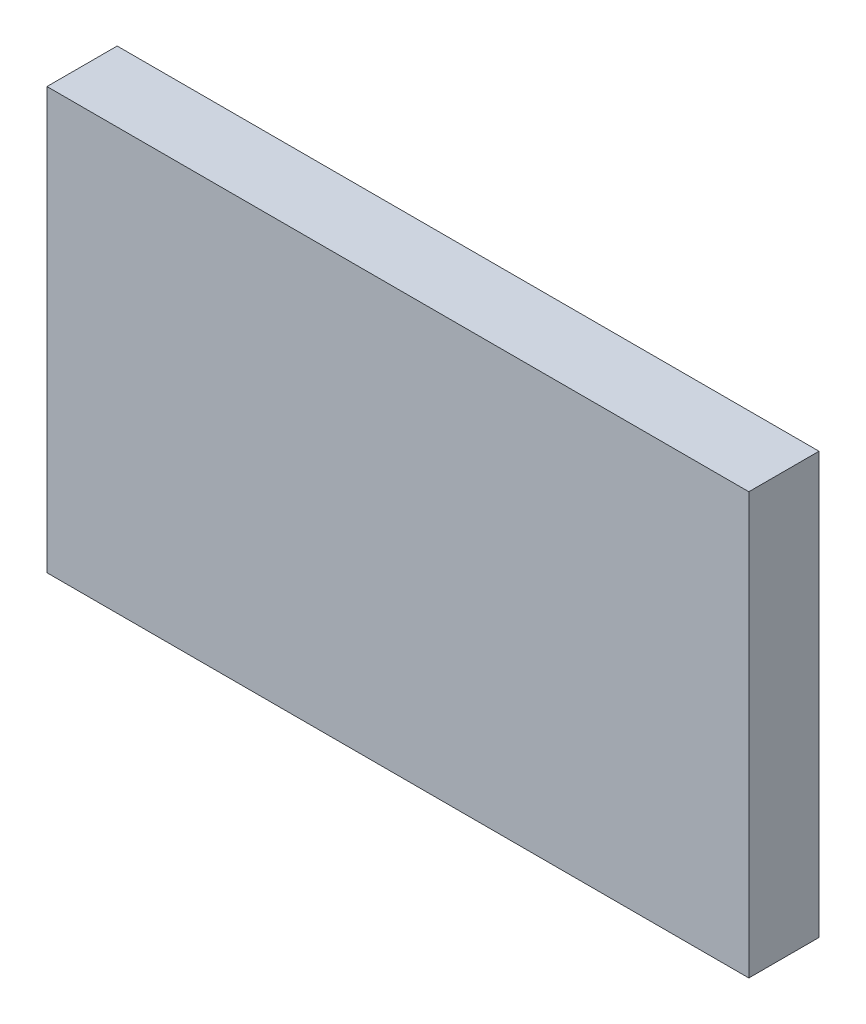
SolidWorks part; units mm, degrees
ref_plane "前视基准面" through (0, 0, 0) normal (0, 0, 1) x (1, 0, 0)
ref_plane "上视基准面" through (0, 0, 0) normal (0, 1, 0) x (1, 0, 0)
ref_plane "右视基准面" through (0, 0, 0) normal (1, 0, 0) x (0, 0, -1)
other "Configuration Table"
sketch "草图1" plane through (0, 0, 0) normal (0, 0, 1) x (1, 0, 0)
  line L1 (-250, -150) -> (250, -150)
  line L2 (-250, -150) -> (-250, 150)
  line L3 (-250, 150) -> (250, 150)
  line L4 (250, -150) -> (250, 150)
  line L5 (-250, -150) -> (250, 150) construction
  line L6 (-250, 150) -> (250, -150) construction
  point P0 (0, 0)
extrude "凸台-拉伸1" add sketch "草图1" along normal blind 50
